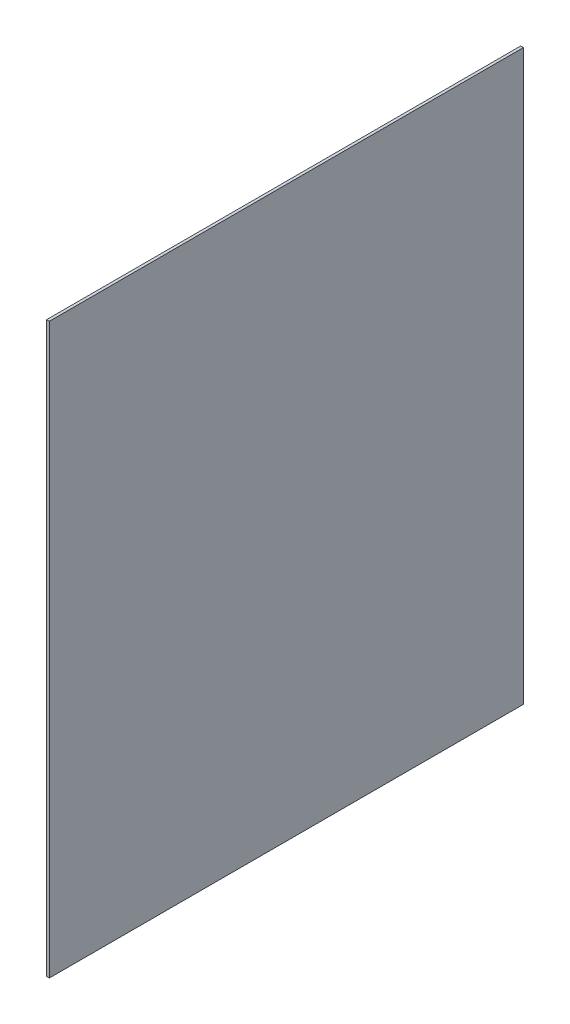
SolidWorks part; units mm, degrees
ref_plane "Front Plane" through (0, 0, 0) normal (0, 0, 1) x (1, 0, 0)
ref_plane "Top Plane" through (0, 0, 0) normal (0, 1, 0) x (1, 0, 0)
ref_plane "Right Plane" through (0, 0, 0) normal (1, 0, 0) x (0, 0, -1)
sketch "Sketch1" plane through (0, 0, 0) normal (0, 0, 1) x (1, 0, 0)
  line L1 (-12.5, -2580.0927) -> (12.5, -2580.0927)
  line L2 (-12.5, -2580.0927) -> (-12.5, 2580.0927)
  line L3 (-12.5, 2580.0927) -> (12.5, 2580.0927)
  line L4 (12.5, -2580.0927) -> (12.5, 2580.0927)
extrude "Boss-Extrude1" add sketch "Sketch1" along normal blind 4300 from offset 2150
